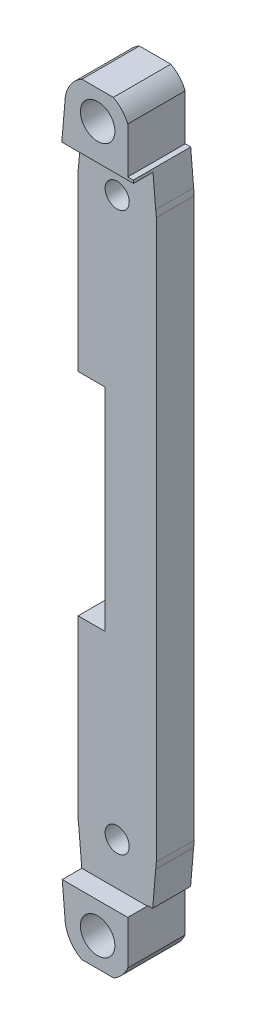
SolidWorks part; units mm, degrees
ref_plane "Спереди" through (0, 0, 0) normal (0, 0, 1) x (1, 0, 0)
ref_plane "Сверху" through (0, 0, 0) normal (0, 1, 0) x (1, 0, 0)
ref_plane "Справа" through (0, 0, 0) normal (1, 0, 0) x (0, 0, -1)
sketch "Skizze1" plane through (0, 0, 0) normal (0, 0, 1) x (1, 0, 0)
  circle A4 centre (-44.1261, -31.0496) radius 2.85
  circle A5 centre (-44.1261, -24.6496) radius 3.4
  circle A6 centre (-44.1261, 23.8904) radius 3.4
  circle A7 centre (-44.1261, 30.2904) radius 2.85
sketch "Skizze5" plane through (0, 0, 0) normal (0, 0, 1) x (1, 0, 0)
  line L0 (-41.2761, 30.2904) -> (-40.7261, 23.8904)
  line L1 (-40.7261, 23.8904) -> (-40.7261, -24.6496)
  line L2 (-40.7261, -24.6496) -> (-41.2761, -31.0496)
  line L3 (-46.9761, -31.0496) -> (-47.5261, -24.6496)
  line L4 (-47.5261, -24.6496) -> (-47.5261, 23.8904)
  line L5 (-47.5261, 23.8904) -> (-46.9761, 30.2904)
  circle A0 centre (-44.1261, -31.0496) radius 2.85 construction
  circle A1 centre (-44.1261, -24.6496) radius 3.4 construction
  circle A2 centre (-44.1261, 23.8904) radius 3.4 construction
  circle A3 centre (-44.1261, 30.2904) radius 2.85 construction
  circle A4 centre (-44.1261, -31.0496) radius 2.85
  circle A5 centre (-44.1261, -24.6496) radius 3.4
  circle A6 centre (-44.1261, 23.8904) radius 3.4
  circle A7 centre (-44.1261, 30.2904) radius 2.85
extrude "Aufsatz-Linear austragen2" add sketch "Skizze5" along normal blind 5 contours A6 L4 A5 L1 | L0 A6 L5 | A7 | A7 L5 A6 L0 | L2 A5 L3 | A5 L3 A4 L2 | A4
sketch "Skizze7" plane through (0, 0, 0) normal (0, 0, -1) x (-1, 0, 0)
  circle A0 centre (44.1261, 30.2904) radius 1.5
  circle A1 centre (44.1261, 23.8904) radius 2.5
  circle A2 centre (44.1261, -24.6496) radius 2.5
  circle A3 centre (44.1261, -31.0496) radius 1.5
  dimension "D1" = 5
  dimension "D2" = 3
  dimension "D3" = 5
  dimension "D4" = 3
extrude "Schnitt-Linear austragen1" cut sketch "Skizze7" against normal blind 5
sketch "Skizze10" plane through (0, 0, 0) normal (0, 0, -1) x (-1, 0, 0)
  circle A0 centre (44.1261, 23.8904) radius 3.4
  circle A1 centre (44.1261, -24.6496) radius 3.4
extrude "Aufsatz-Linear austragen4" add sketch "Skizze10" against normal blind 5
sketch "Skizze11" plane through (0, 0, 0) normal (0, 0, -1) x (-1, 0, 0)
  circle A0 centre (44.1261, -24.6496) radius 1.05
  circle A1 centre (44.1261, 23.8904) radius 1.05
  dimension "D1" = 2.1
extrude "Schnitt-Linear austragen3" cut sketch "Skizze11" against normal blind 5
sketch "Skizze15" plane through (0, 0, 0) normal (0, 0, -1) x (-1, 0, 0)
  circle A0 centre (44.1261, 30.2904) radius 2.25
  circle A1 centre (44.1261, -31.0496) radius 2.25
  dimension "D1" = 4.5
extrude "Schnitt-Linear austragen7" cut sketch "Skizze15" against normal blind 2
sketch "Skizze16" plane through (0, 0, 5) normal (0, 0, 1) x (1, 0, 0)
  line L1 (-48.4348, 27.1798) -> (-40.0659, 27.1798)
  line L2 (-48.4348, 27.1798) -> (-48.4348, -28.3565)
  line L3 (-48.4348, -28.3565) -> (-40.0659, -28.3565)
  line L4 (-40.0659, 27.1798) -> (-40.0659, -28.3565)
extrude "Schnitt-Linear austragen8" cut sketch "Skizze16" against normal blind 1.7
sketch "Skizze17" plane through (0, 0, 0) normal (0, 0, -1) x (-1, 0, 0)
  line L0 (47.5261, -24.6496) -> (47.5261, 23.8904) construction
  line L1 (47.5261, 8.9056) -> (45.195, 8.9056)
  line L2 (47.5261, 8.9056) -> (47.5261, -9.4969)
  line L3 (47.5261, -9.4969) -> (45.195, -9.4969)
  line L4 (45.195, 8.9056) -> (45.195, -9.4969)
  line L6 (41.0799, 34.5001) -> (47.8845, 34.5001)
  line L7 (41.0799, 34.5001) -> (41.0799, 32.7912)
  line L8 (41.0799, 32.7912) -> (47.8845, 32.7912)
  line L9 (47.8845, 34.5001) -> (47.8845, 32.7912)
  line L10 (39.751, -36.1084) -> (48.7584, -36.1084)
  line L11 (39.751, -36.1084) -> (39.751, -33.5324)
  line L12 (39.751, -33.5324) -> (48.7584, -33.5324)
  line L13 (48.7584, -36.1084) -> (48.7584, -33.5324)
  line L14 (39.5854, 32.4824) -> (41.5056, 32.4824)
  line L15 (39.5854, 32.4824) -> (39.5854, 27.4189)
  line L16 (39.5854, 27.4189) -> (41.5056, 27.4189)
  line L17 (41.5056, 32.4824) -> (41.5056, 27.4189)
  line L18 (39.5854, -32.577) -> (41.5056, -32.577)
  line L19 (39.5854, -32.577) -> (39.5854, -28.2901)
  line L20 (39.5854, -28.2901) -> (41.5056, -28.2901)
  line L21 (41.5056, -32.577) -> (41.5056, -28.2901)
extrude "Schnitt-Linear austragen9" cut sketch "Skizze17" against normal blind 11.7
